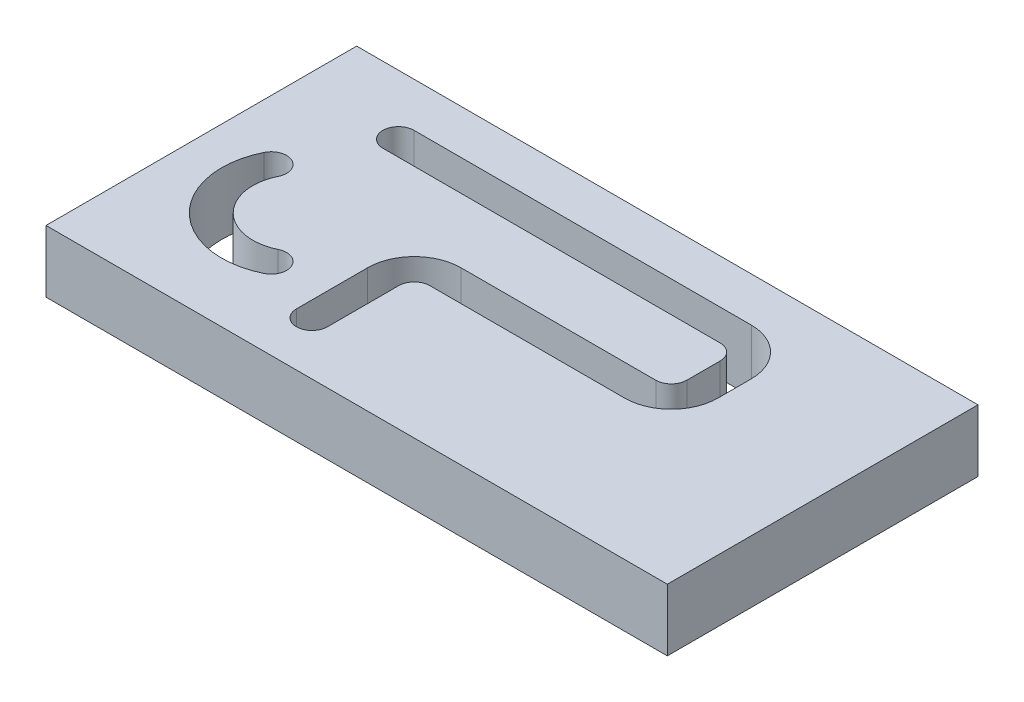
SolidWorks part; units mm, degrees
ref_plane "Front Plane" through (0, 0, 0) normal (0, 0, 1) x (1, 0, 0)
ref_plane "Top Plane" through (0, 0, 0) normal (0, 1, 0) x (1, 0, 0)
ref_plane "Right Plane" through (0, 0, 0) normal (1, 0, 0) x (0, 0, -1)
sketch "Sketch1" plane through (0, 0, 0) normal (0, 1, 0) x (1, 0, 0)
  line L1 (127, -63.5) -> (-127, -63.5)
  line L2 (127, -63.5) -> (127, 63.5)
  line L3 (127, 63.5) -> (-127, 63.5)
  line L4 (-127, -63.5) -> (-127, 63.5)
  line L5 (127, -63.5) -> (-127, 63.5) construction
  line L6 (127, 63.5) -> (-127, -63.5) construction
  point P0 (0, 0)
  dimension "D1" = 254
  dimension "D2" = 127
extrude "Boss-Extrude1" add sketch "Sketch1" along normal blind 25.4
sketch "Sketch3" plane through (0, 25.4, 0) normal (0, 1, 0) x (1, 0, 0)
  line L0 (-85.4662, 39.0448) -> (52.4171, 39.0448) construction
  line L1 (65.1171, 26.3448) -> (65.1171, 12.7) construction
  line L2 (52.4171, 0) -> (-27.2351, 0) construction
  line L3 (-39.9351, -12.7) -> (-39.9351, -41.8428) construction
  line L4 (-85.4662, 32.6948) -> (52.4171, 32.6948)
  line L5 (58.7671, 26.3448) -> (58.7671, 12.7)
  line L6 (52.4171, 6.35) -> (-27.2351, 6.35)
  line L7 (-46.2851, -12.7) -> (-46.2851, -41.8428)
  line L8 (-85.4662, 45.3948) -> (52.4171, 45.3948)
  line L9 (71.4671, 26.3448) -> (71.4671, 12.7)
  line L10 (52.4171, -6.35) -> (-27.2351, -6.35)
  line L11 (-33.5851, -12.7) -> (-33.5851, -41.8428)
  arc A0 (-27.2351, 0) -> (-39.9351, -12.7) centre (-27.2351, -12.7) ccw construction
  arc A1 (65.1171, 12.7) -> (52.4171, 0) centre (52.4171, 12.7) cw construction
  arc A2 (52.4171, 39.0448) -> (65.1171, 26.3448) centre (52.4171, 26.3448) cw construction
  arc A3 (52.4171, 32.6948) -> (58.7671, 26.3448) centre (52.4171, 26.3448) cw
  arc A4 (58.7671, 12.7) -> (52.4171, 6.35) centre (52.4171, 12.7) cw
  arc A5 (-27.2351, 6.35) -> (-46.2851, -12.7) centre (-27.2351, -12.7) ccw
  arc A6 (52.4171, 45.3948) -> (71.4671, 26.3448) centre (52.4171, 26.3448) cw
  arc A7 (71.4671, 12.7) -> (52.4171, -6.35) centre (52.4171, 12.7) cw
  arc A8 (-27.2351, -6.35) -> (-33.5851, -12.7) centre (-27.2351, -12.7) ccw
  arc A9 (-85.4662, 32.6948) -> (-85.4662, 45.3948) centre (-85.4662, 39.0448) cw
  arc A10 (-46.2851, -41.8428) -> (-33.5851, -41.8428) centre (-39.9351, -41.8428) ccw
  dimension "D1" = 12.7
  dimension "D2" = 6.35
  dimension "D3" = 6.35
extrude "Cut-Extrude2" cut sketch "Sketch3" against normal through all
sketch "Sketch4" plane through (0, 25.4, 0) normal (0, 1, 0) x (1, 0, 0)
  arc A0 (-102.6099, 4.1154) -> (-68.2511, -30.2433) centre (-79.4839, -7.1174) ccw construction
  arc A1 (-108.3217, 6.8897) -> (-65.4768, -35.9552) centre (-79.4839, -7.1174) ccw
  arc A2 (-96.898, 1.341) -> (-71.0255, -24.5315) centre (-79.4839, -7.1174) ccw
  arc A3 (-96.898, 1.341) -> (-108.3217, 6.8897) centre (-102.6099, 4.1154) ccw
  arc A4 (-65.4768, -35.9552) -> (-71.0255, -24.5315) centre (-68.2511, -30.2433) ccw
  point P3 (-97.6633, -25.2968)
  dimension "D1" = 6.35
extrude "Cut-Extrude3" cut sketch "Sketch4" against normal through all
